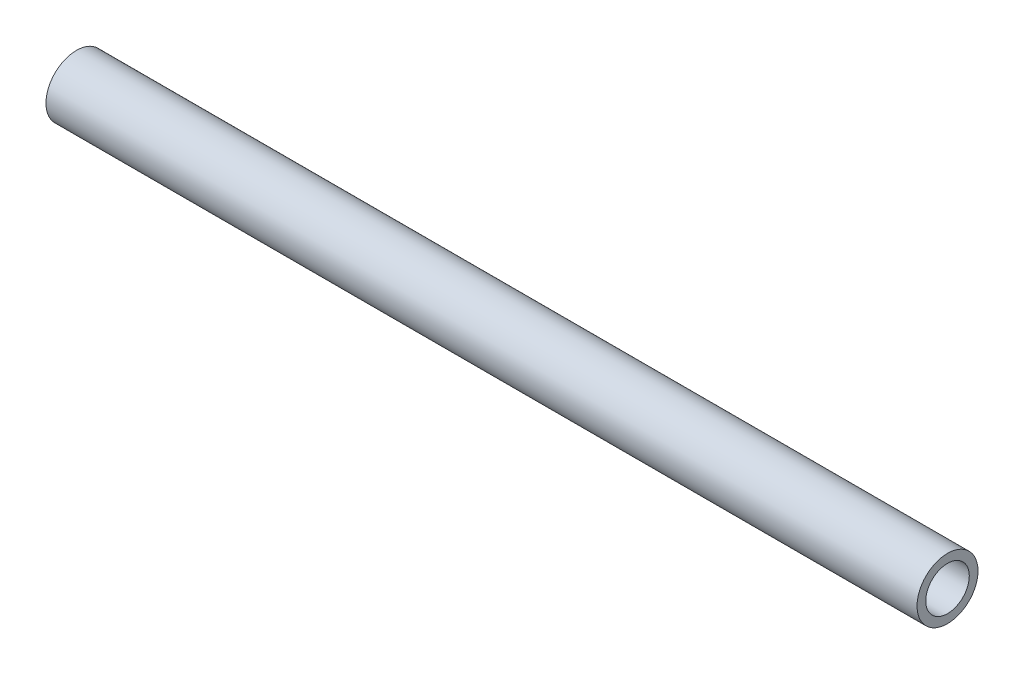
SolidWorks part; units mm, degrees
ref_plane "Front" through (0, 0, 0) normal (0, 0, 1) x (1, 0, 0)
ref_plane "Top" through (0, 0, 0) normal (0, 1, 0) x (1, 0, 0)
ref_plane "Right" through (0, 0, 0) normal (1, 0, 0) x (0, 0, -1)
sketch "Sketch1" plane through (0, 0, 0) normal (1, 0, 0) x (0, 0, -1)
  circle A0 centre (0, 0) radius 4.445
  circle A1 centre (0, 0) radius 3.175
  dimension "D1" = 8.89
  dimension "D2" = 6.35
extrude "Boss-Extrude1" add sketch "Sketch1" along normal mid plane 127
